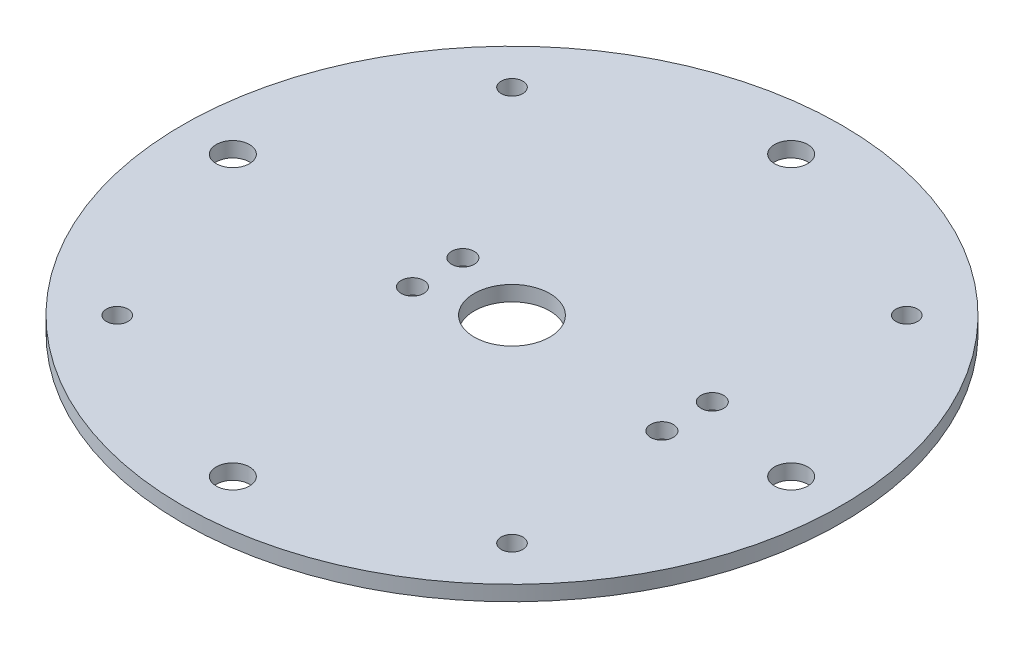
SolidWorks part; units mm, degrees
ref_plane "Front Plane" through (0, 0, 0) normal (0, 0, 1) x (1, 0, 0)
ref_plane "Top Plane" through (0, 0, 0) normal (0, 1, 0) x (1, 0, 0)
ref_plane "Right Plane" through (0, 0, 0) normal (1, 0, 0) x (0, 0, -1)
sketch "Sketch1" plane through (0, 0, 0) normal (0, 1, 0) x (1, 0, 0)
  circle A0 centre (0, 0) radius 65.4
  dimension "Diameter" = 130.8
extrude "Boss-Extrude1" add sketch "Sketch1" along normal mid plane 3
hole_wizard "M6 Clearance Hole1" positions "Sketch8" profile "Sketch9" hole size "M6" standard "ANSI Metric" end condition up to next
sketch "Sketch8" plane through (0, 1.5, 0) normal (0, 1, 0) x (1, 0, 0)
  line L0 (0, 0) -> (55.4, 0) construction
  point P0 (55.4, 0)
  dimension "ThreadedHoleDistance" = 55.4
sketch "Sketch9" plane through (55.4, 1.5, 0) normal (1, 0, 0) x (0, 0, 1)
  line L0 (0, 0) -> (0, 3)
  line L1 (0, 3) -> (3.3, 3)
  line L2 (3.3, 3) -> (3.3, 0)
  line L5 (3.3, 0) -> (0, 0)
  line L11 (0, -6.35) -> (0, 107.95) construction
  dimension "Thru Hole Dia." = 6.6
  dimension "Thru Hole Depth" = 3
pattern_circular "CirPattern2" count 4 over 360 about axis through (0, 0, 0) along (0, 1, 0) of "M6 Clearance Hole1"
sketch "Sketch5" plane through (0, 1.5, 0) normal (0, 1, 0) x (1, 0, 0)
  line L0 (0, 0) -> (65.4, 0) construction
  line L2 (0, 0) -> (39.1737, 39.1737) construction
  circle A0 centre (0, 0) radius 65.4 construction
  dimension "D1" = 45
  dimension " NoseShellHoleRadius" = 55.4
hole_wizard "M4 Clearance Hole1" positions "Sketch6" profile "Sketch7" hole size "M4" standard "ANSI Metric" end condition up to next
sketch "Sketch6" plane through (0, 1.5, 0) normal (0, 1, 0) x (1, 0, 0)
  point P0 (39.1737, 39.1737)
sketch "Sketch7" plane through (39.1737, 1.5, -39.1737) normal (1, 0, 0) x (0, 0, 1)
  line L0 (0, 0) -> (0, 3)
  line L1 (0, 3) -> (2.15, 3)
  line L2 (2.15, 3) -> (2.15, 0)
  line L5 (2.15, 0) -> (0, 0)
  line L11 (0, -6.35) -> (0, 107.95) construction
  dimension "Thru Hole Dia." = 4.3
  dimension "Thru Hole Depth" = 3
pattern_circular "CirPattern1" count 4 over 360 about axis through (0, 0, 0) along (0, 1, 0) of "M4 Clearance Hole1"
sketch "Sketch10" plane through (0, 1.5, 0) normal (0, 1, 0) x (1, 0, 0)
  circle A0 centre (0, 0) radius 7.5
  dimension "D1" = 15
extrude "Cut-Extrude1" cut sketch "Sketch10" against normal through all
sketch "Sketch11" plane through (0, -1.5, 0) normal (0, -1, 0) x (1, 0, 0)
  circle A0 centre (-14.75, -5) radius 2.25
  arc A1 (-16.7656, -6) -> (-16.7656, -4) centre (-14.75, -5) ccw construction
  circle A2 centre (-14.75, 5) radius 2.25
  circle A3 centre (34.75, -5) radius 2.25
  circle A4 centre (34.75, 5) radius 2.25
  arc A5 (-16.7656, 4) -> (-16.7656, 6) centre (-14.75, 5) ccw construction
  arc A6 (36.7656, 6) -> (36.7656, 4) centre (34.75, 5) ccw construction
  arc A7 (36.7656, -4) -> (36.7656, -6) centre (34.75, -5) ccw construction
extrude "Cut-Extrude2" cut sketch "Sketch11" against normal through all
sketch "Sketch12" plane through (0, 1.5, 0) normal (0, 1, 0) x (1, 0, 0)
  circle A0 centre (0, 0) radius 65.4 construction
  circle A1 centre (0, 0) radius 65.4
